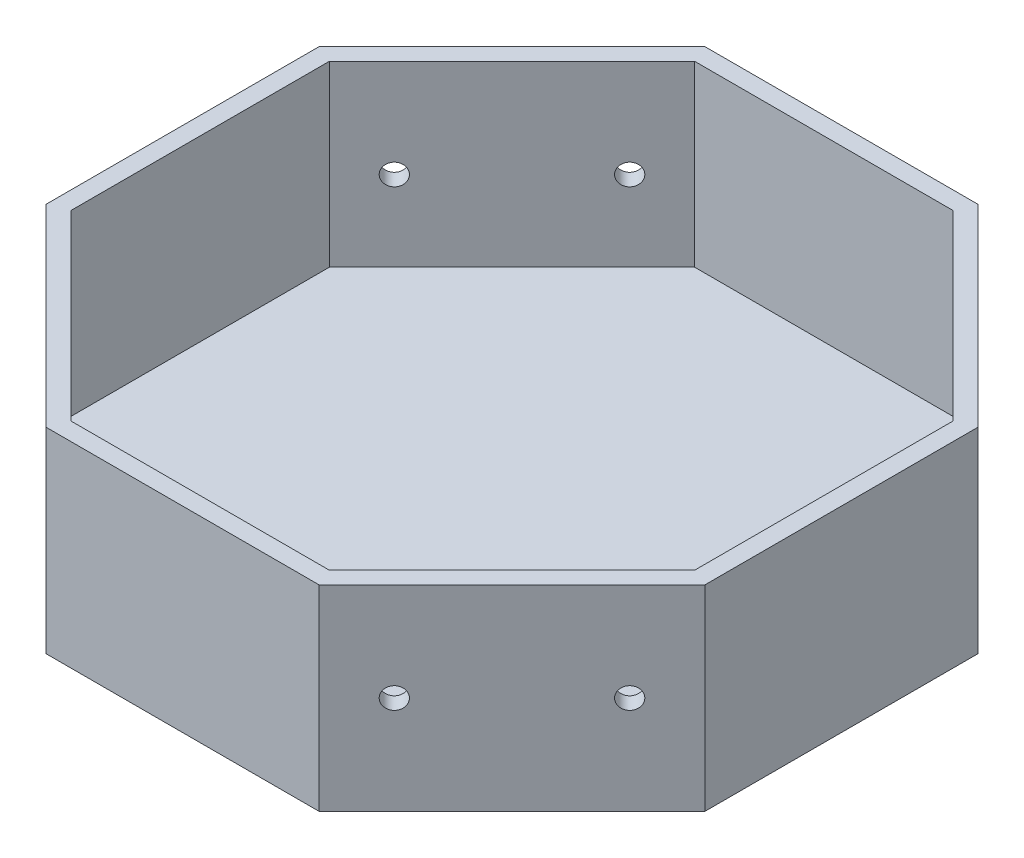
SolidWorks part; units mm, degrees
ref_plane "Plano frontal" through (0, 0, 0) normal (0, 0, 1) x (1, 0, 0)
ref_plane "Plano superior" through (0, 0, 0) normal (0, 1, 0) x (1, 0, 0)
ref_plane "Plano direito" through (0, 0, 0) normal (1, 0, 0) x (0, 0, -1)
sketch "Sketch1" plane through (0, 0, 0) normal (0, 1, 0) x (1, 0, 0)
  line L1 (55.4328, 22.961) -> (22.961, 55.4328)
  line L2 (22.961, 55.4328) -> (-22.961, 55.4328)
  line L3 (-22.961, 55.4328) -> (-55.4328, 22.961)
  line L4 (-55.4328, 22.961) -> (-55.4328, -22.961)
  line L5 (-55.4328, -22.961) -> (-22.961, -55.4328)
  line L6 (-22.961, -55.4328) -> (22.961, -55.4328)
  line L7 (22.961, -55.4328) -> (55.4328, -22.961)
  line L8 (55.4328, -22.961) -> (55.4328, 22.961)
  circle A0 centre (0, 0) radius 55.4328 construction
  dimension "D1" = 120
extrude "Boss-Extrude1" add sketch "Sketch1" along normal blind 3
sketch "Sketch2" plane through (0, 3, 0) normal (0, 1, 0) x (1, 0, 0)
  line L16 (52.4328, -21.7184) -> (52.4328, 21.7184)
  line L17 (52.4328, 21.7184) -> (21.7184, 52.4328)
  line L18 (21.7184, 52.4328) -> (-21.7184, 52.4328)
  line L19 (-21.7184, 52.4328) -> (-52.4328, 21.7184)
  line L20 (-52.4328, 21.7184) -> (-52.4328, -21.7184)
  line L21 (-52.4328, -21.7184) -> (-21.7184, -52.4328)
  line L22 (-21.7184, -52.4328) -> (21.7184, -52.4328)
  line L23 (21.7184, -52.4328) -> (52.4328, -21.7184)
  line L24 (52.4328, -21.7184) -> (52.4328, 21.7184)
  line L25 (52.4328, 21.7184) -> (21.7184, 52.4328)
  line L26 (21.7184, 52.4328) -> (-21.7184, 52.4328)
  line L27 (-21.7184, 52.4328) -> (-52.4328, 21.7184)
  line L28 (-52.4328, 21.7184) -> (-52.4328, -21.7184)
  line L29 (-52.4328, -21.7184) -> (-21.7184, -52.4328)
  line L30 (-21.7184, -52.4328) -> (21.7184, -52.4328)
  line L31 (21.7184, -52.4328) -> (52.4328, -21.7184)
  line L32 (55.4328, -22.961) -> (55.4328, 22.961)
  line L33 (55.4328, 22.961) -> (22.961, 55.4328)
  line L34 (22.961, 55.4328) -> (-22.961, 55.4328)
  line L35 (-22.961, 55.4328) -> (-55.4328, 22.961)
  line L36 (-55.4328, 22.961) -> (-55.4328, -22.961)
  line L37 (-55.4328, -22.961) -> (-22.961, -55.4328)
  line L38 (-22.961, -55.4328) -> (22.961, -55.4328)
  line L39 (22.961, -55.4328) -> (55.4328, -22.961)
  line L40 (55.4328, -22.961) -> (55.4328, 22.961)
  line L41 (55.4328, 22.961) -> (22.961, 55.4328)
  line L42 (22.961, 55.4328) -> (-22.961, 55.4328)
  line L43 (-22.961, 55.4328) -> (-55.4328, 22.961)
  line L44 (-55.4328, 22.961) -> (-55.4328, -22.961)
  line L45 (-55.4328, -22.961) -> (-22.961, -55.4328)
  line L46 (-22.961, -55.4328) -> (22.961, -55.4328)
  line L47 (22.961, -55.4328) -> (55.4328, -22.961)
  dimension "D1" = 3
  dimension "D2" = 0
extrude "Boss-Extrude2" add sketch "Sketch2" along normal blind 30
sketch "Sketch3" plane through (39.1969, 0, 39.1969) normal (0.7071, 0, 0.7071) x (0.7071, 0, -0.7071)
  line L0 (-22.961, 33) -> (22.961, 33) construction
  line L1 (-22.961, 33) -> (-22.961, 0) construction
  circle A0 centre (-14, 16.5) radius 1.8
  circle A1 centre (14, 16.5) radius 1.8
  point P7 (0, 33)
  point P10 (-22.961, 16.5)
  dimension "D1" = 3.6
  dimension "D2" = 3.6
  dimension "D3" = 14
  dimension "D4" = 14
extrude "Cut-Extrude1" cut sketch "Sketch3" against normal up to next
sketch "Sketch4" plane through (0, 0, 0) normal (0, 0, 1) x (1, 0, 0)
  line L0 (0, 0) -> (0, 54.8002) construction
pattern_circular "CirPattern1" count 4 every 90 about axis through (0, 0, 0) along (0, 1, 0) of "Cut-Extrude1"
equation "\"D2@Sketch3\"=\"D1@Sketch3\""
